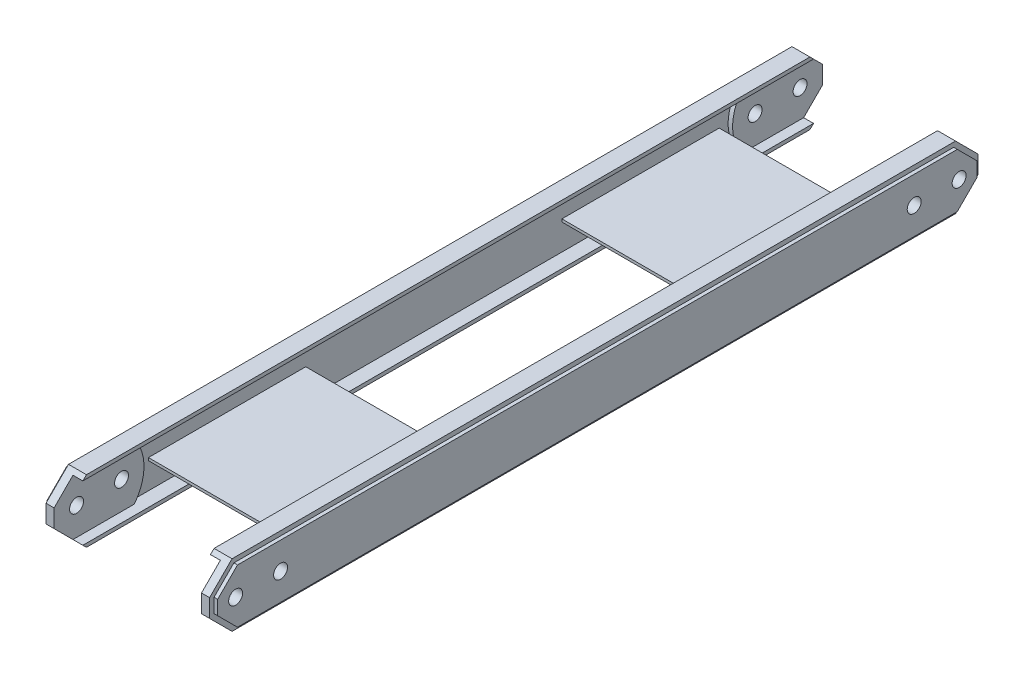
SolidWorks part; units mm, degrees
ref_plane "前视基准面" through (0, 0, 0) normal (0, 0, 1) x (1, 0, 0)
ref_plane "上视基准面" through (0, 0, 0) normal (0, 1, 0) x (1, 0, 0)
ref_plane "右视基准面" through (0, 0, 0) normal (1, 0, 0) x (0, 0, -1)
sketch "草图1" plane through (0, 0, 0) normal (0, 0, 1) x (1, 0, 0)
  line L0 (-1000, 0) -> (49000, 0) construction
  line L1 (-190, 70) -> (-150, 70)
  line L2 (-190, 70) -> (-190, -70)
  line L3 (-190, -70) -> (-150, -70)
  line L4 (-150, 70) -> (-150, -70)
  line L5 (0, -1000) -> (0, 49000) construction
  line L7 (-182, 62) -> (-150, 62)
  line L8 (-182, 62) -> (-182, -62)
  line L9 (-182, -62) -> (-150, -62)
  line L10 (-150, 62) -> (-150, -62)
  dimension "D1" = 140
  dimension "D2" = 8
  dimension "D3" = 8
  dimension "D4" = 40
  dimension "D5" = 70
  dimension "D6" = 190
  dimension "D7" = 8
extrude "拉伸1" add sketch "草图1" along normal blind 855 contours L9 L8 L7 L4 L1 L2 L3
sketch "草图2" plane through (-182, 0, 0) normal (1, 0, 0) x (0, 0, -1)
  line L0 (-3189, 0) -> (46811, 0) construction
  line L1 (-855, 62) -> (-855, -62) construction
  line L2 (-855, -62) -> (0, -62) construction
  line L3 (-855, 62) -> (0, 62) construction
  line L4 (-676.5398, 62) -> (-855, 62)
  line L5 (-855, 62) -> (-855, -62)
  line L6 (-855, -62) -> (-676.5398, -62)
  arc A0 (-676.5398, 62) -> (-676.5398, -62) centre (-755, 0) cw
  point P5 (-855, 0)
  dimension "D1" = 100
  dimension "D2" = 100
extrude "拉伸2" add sketch "草图2" along normal blind 10
sketch "草图3" plane through (-182, 0, 0) normal (1, 0, 0) x (0, 0, -1)
  line L0 (-1655, 0) -> (48345, 0) construction
  line L1 (-855, 62) -> (-855, -62) construction
  line L2 (-635, 2) -> (-285, 2)
  line L3 (-635, 2) -> (-635, -4)
  line L4 (-635, -4) -> (-285, -4)
  line L5 (-285, 2) -> (-285, -4)
  arc A0 (-676.5398, -62) -> (-676.5398, 62) centre (-755, 0) ccw construction
  point P6 (-655, 0)
  dimension "D1" = 220
  dimension "D2" = 4
  dimension "D3" = 4
  dimension "D4" = 350
extrude "拉伸3" add sketch "草图3" along normal blind 174
mirror "镜向1" about plane through (-8, -4, 635) normal (1, 0, 0) of bodies 107
sketch "草图8" plane through (-190, 0, 0) normal (-1, 0, 0) x (0, 0, 1)
  line L0 (-145, 0) -> (49855, 0) construction
  line L1 (855, 70) -> (855, -70) construction
  line L2 (805, 70) -> (855, 70)
  line L3 (855, 70) -> (0, 70) construction
  line L4 (855, 70) -> (855, 20)
  line L5 (855, 20) -> (805, 70)
  line L6 (855, -70) -> (855, -20)
  line L7 (805, -70) -> (855, -70)
  line L8 (855, -20) -> (805, -70)
  point P5 (855, 0)
  dimension "D1" = 50
  dimension "D2" = 50
extrude "拉伸9" cut sketch "草图8" against normal through all
mirror "镜向2" about plane through (0, 0, 0) normal (0, 0, 1) of bodies 116 111
sketch "草图6" plane through (-190, 0, 0) normal (-1, 0, 0) x (0, 0, 1)
  line L0 (-1855, 0) -> (48145, 0) construction
  line L1 (-855, 20) -> (-855, -20) construction
  line L2 (0, -930) -> (0, 49070) construction
  line L3 (805, 70) -> (-805, 70) construction
  line L4 (-800.8579, 60) -> (-845, 15.8579)
  line L5 (-845, 15.8579) -> (-845, -15.8579)
  line L6 (-845, -15.8579) -> (-800.8579, -60)
  line L9 (-800.8579, 60) -> (800.8579, 60)
  line L10 (-800.8579, -60) -> (800.8579, -60)
  line L11 (805, -70) -> (-805, -70) construction
  line L12 (845, -15.8579) -> (800.8579, -60)
  line L13 (845, 15.8579) -> (845, -15.8579)
  line L14 (800.8579, 60) -> (845, 15.8579)
  line L15 (805, 70) -> (855, 20) construction
  line L16 (-805, 70) -> (-855, 20) construction
  line L17 (-855, -20) -> (-805, -70) construction
  point P5 (-855, 0)
  point P10 (0, 70)
  point P14 (-830, 45)
  point P23 (0, 60)
  point P24 (0, -60)
  point P26 (830, 45)
  dimension "D1" = 10
  dimension "D2" = 10
  dimension "D3" = 10
  dimension "D4" = 10
  dimension "D5" = 10
  dimension "D6" = 10
extrude "拉伸7" add sketch "草图6" along normal blind 8
sketch "草图9" plane through (-198, 0, 0) normal (-1, 0, 0) x (0, 0, 1)
  line L0 (-1855, 0) -> (48145, 0) construction
  line L1 (-855, 20) -> (-855, -20) construction
  line L2 (0, -1070) -> (0, 48930) construction
  line L3 (805, -70) -> (-805, -70) construction
  circle A0 centre (-805, 0) radius 15.5
  circle A1 centre (-705, 0) radius 15.5
  circle A2 centre (705, 0) radius 15.5
  circle A3 centre (805, 0) radius 15.5
  point P5 (-855, 0)
  point P15 (0, -70)
  dimension "D1" = 31
  dimension "D2" = 50
  dimension "D3" = 100
pattern_linear "阵列(线性)1" count 2 spacing 372 along (1, 0, 0) of "拉伸7"
extrude "拉伸10" cut sketch "草图9" against normal through all
